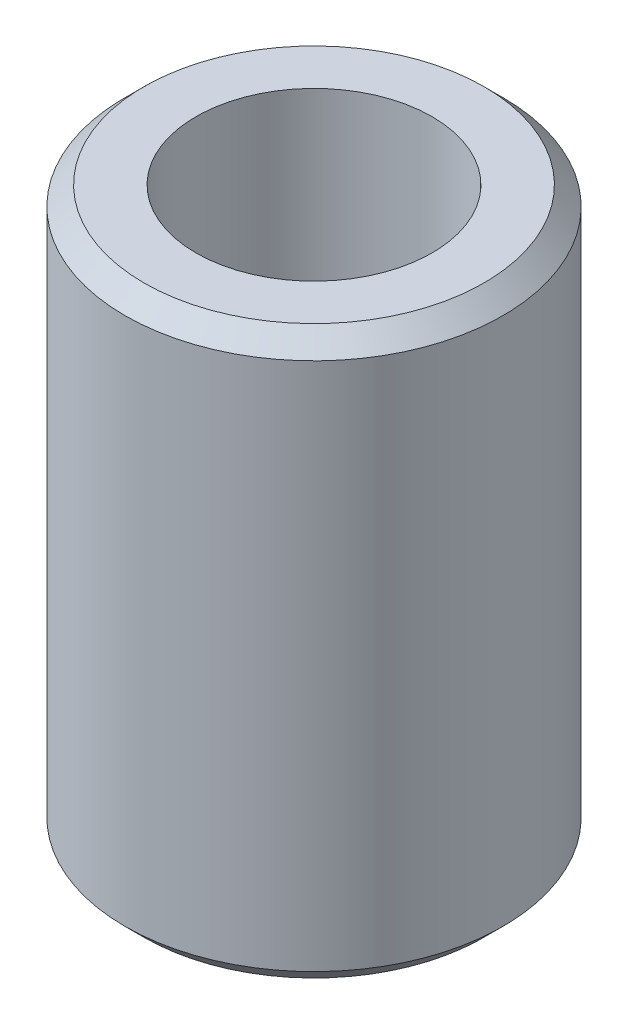
SolidWorks part; units mm, degrees
ref_plane "Front Plane" through (0, 0, 0) normal (0, 0, 1) x (1, 0, 0)
ref_plane "Top Plane" through (0, 0, 0) normal (0, 1, 0) x (1, 0, 0)
ref_plane "Right Plane" through (0, 0, 0) normal (1, 0, 0) x (0, 0, -1)
sketch "Sketch2" plane through (0, 0, 0) normal (0, 1, 0) x (1, 0, 0)
  circle A0 centre (0, 0) radius 12.5
  circle A1 centre (0, 0) radius 20
  point P5 (0, 0)
  dimension "D1" = 40
  dimension "D2" = 25
extrude "Boss-Extrude1" add sketch "Sketch2" along normal mid plane 60
chamfer "Chamfer1" distance 2 angle 45 2 edges at (0, -30, 20) (0, 30, 20)
